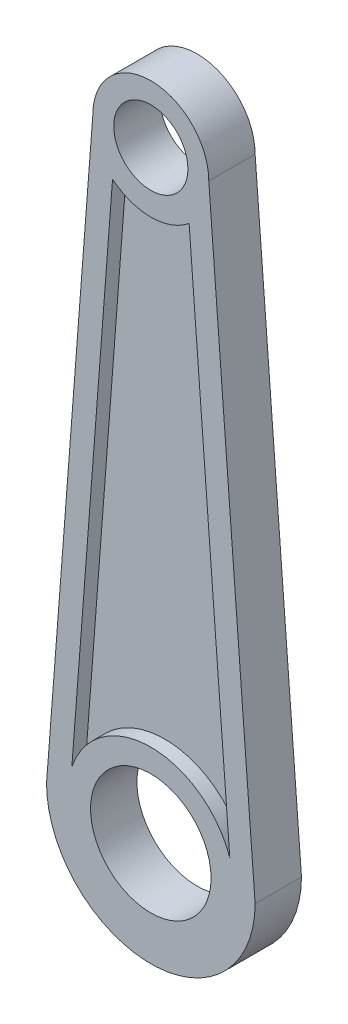
SolidWorks part; units mm, degrees
ref_plane "Front Plane" through (0, 0, 0) normal (0, 0, 1) x (1, 0, 0)
ref_plane "Top Plane" through (0, 0, 0) normal (0, 1, 0) x (1, 0, 0)
ref_plane "Right Plane" through (0, 0, 0) normal (1, 0, 0) x (0, 0, -1)
sketch "Sketch2" plane through (0, 0, 0) normal (0, 0, 1) x (1, 0, 0)
  line L0 (-22.5, 0) -> (-12.5, 130)
  line L1 (12.5, 130) -> (22.5, 0)
  circle A0 centre (0, 0) radius 22.5
  circle A1 centre (0, 0) radius 13
  circle A2 centre (0, 130) radius 12.5
  circle A3 centre (0, 130) radius 8
  dimension "D2" = 45
  dimension "D3" = 26
  dimension "D4" = 16
  dimension "D5" = 25
  dimension "D1" = 130
extrude "Boss-Extrude1" add sketch "Sketch2" along normal mid plane 10 contours A2 A3 | A2 L0 A0 L1 | L1 A0 L0 A1
sketch "Sketch3" plane through (0, 0, 5) normal (0, 0, 1) x (1, 0, 0)
  line L4 (-7.4981, 129.8323) -> (-17.4991, -0.18)
  line L5 (17.4991, -0.18) -> (7.4981, 129.8323)
  line L6 (-8.2576, 119.9595) -> (-17.0388, 5.8033)
  line L7 (17.0388, 5.8033) -> (8.2576, 119.9595)
  arc A4 (7.4981, 129.8323) -> (-7.4981, 129.8323) centre (0, 130) ccw
  arc A5 (-17.4991, -0.18) -> (17.4991, -0.18) centre (0, 0) ccw
  circle A8 centre (0, 130) radius 13
  arc A9 (-8.2576, 119.9595) -> (8.2576, 119.9595) centre (0, 130) ccw
  circle A11 centre (0, 0) radius 18
  arc A12 (17.0388, 5.8033) -> (-17.0388, 5.8033) centre (0, 0) ccw
  dimension "D1" = 5
  dimension "D2" = 5
  dimension "D3" = 5
extrude "Cut-Extrude1" cut sketch "Sketch3" against normal blind 3 contours L6 A12 L7 A9
mirror "Mirror1" about plane through (0, 0, 0) normal (0, 0, 1) of "Cut-Extrude1"
